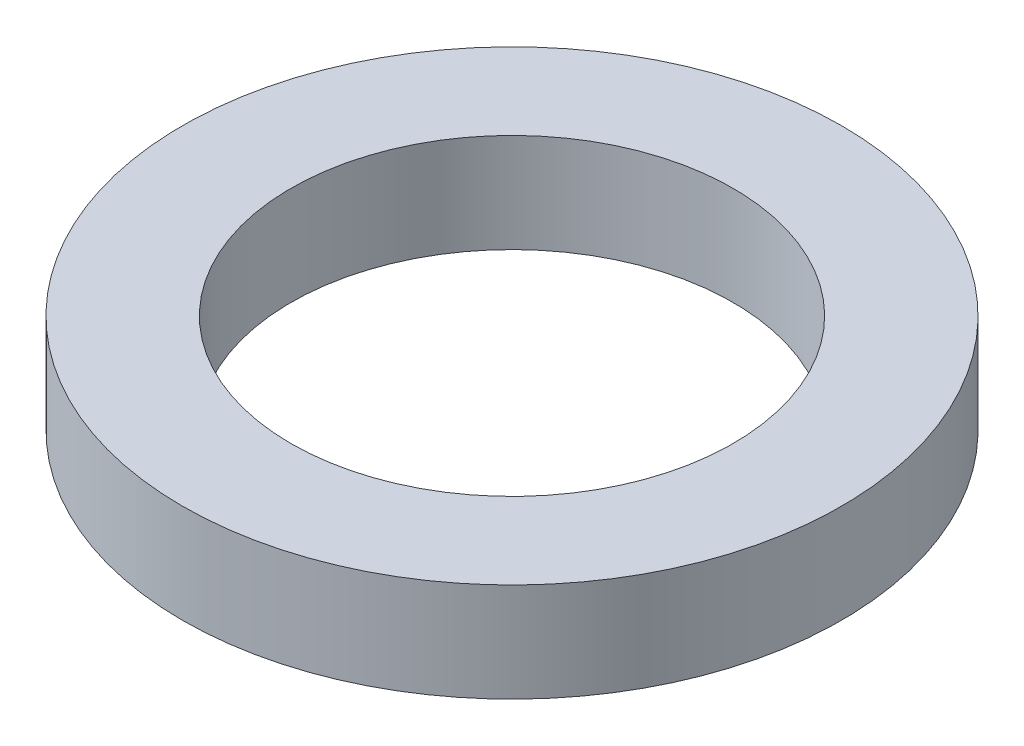
SolidWorks part; units mm, degrees
ref_plane "정면" through (0, 0, 0) normal (0, 0, 1) x (1, 0, 0)
ref_plane "윗면" through (0, 0, 0) normal (0, 1, 0) x (1, 0, 0)
ref_plane "우측면" through (0, 0, 0) normal (1, 0, 0) x (0, 0, -1)
ref_plane "평면1" through (0, 0, 0) normal (0, 0, -1) x (-1, 0, 0)
sketch "스케치1" plane through (0, 0, 0) normal (0, 0, -1) x (-1, 0, 0)
  line L0 (-4.025, 1.8) -> (-6, 1.8)
  line L1 (-6, 1.8) -> (-6, 0)
  line L2 (-6, 0) -> (-4.025, 0)
  line L3 (-4.025, 0) -> (-4.025, 1.8)
  line L4 (0, 0) -> (0, 1.9) construction
  dimension "D1" = 4.025
  dimension "D2" = 6
  dimension "D3" = 1.8
revolve "회전1" add sketch "스케치1" angle 360 about L4
